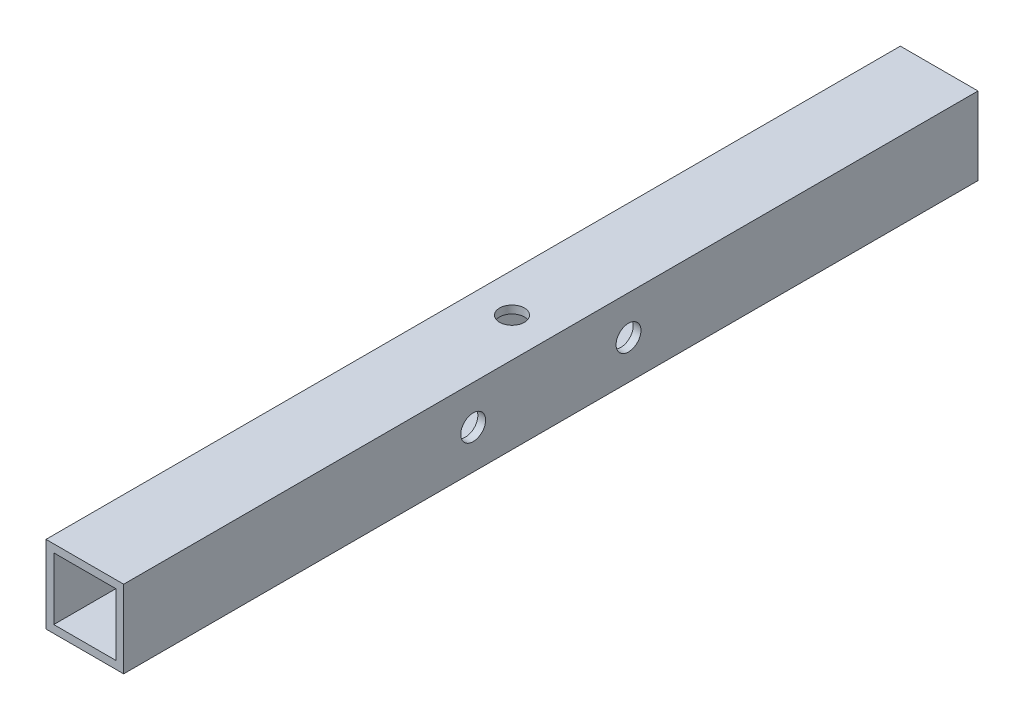
SolidWorks part; units mm, degrees
ref_plane "正面" through (0, 0, 0) normal (0, 0, 1) x (1, 0, 0)
ref_plane "平面" through (0, 0, 0) normal (0, 1, 0) x (1, 0, 0)
ref_plane "右側面" through (0, 0, 0) normal (1, 0, 0) x (0, 0, -1)
sketch "ｽｹｯﾁ1" plane through (0, 0, 0) normal (0, 0, 1) x (1, 0, 0)
  line L1 (-5, -5) -> (5, -5)
  line L2 (-5, -5) -> (-5, 5)
  line L3 (-5, 5) -> (5, 5)
  line L4 (5, -5) -> (5, 5)
  line L5 (-5, -5) -> (5, 5) construction
  line L6 (-5, 5) -> (5, -5) construction
  line L7 (-4, -4) -> (4, -4)
  line L8 (-4, -4) -> (-4, 4)
  line L9 (-4, 4) -> (4, 4)
  line L10 (4, -4) -> (4, 4)
  line L11 (-4, -4) -> (4, 4) construction
  line L12 (-4, 4) -> (4, -4) construction
  point P0 (0, 0)
  point P6 (0, 0)
  dimension "D1" = 10
  dimension "D2" = 10
  dimension "D3" = 1
extrude "ﾎﾞｽ - 押し出し1" add sketch "ｽｹｯﾁ1" along normal blind 110
sketch "ｽｹｯﾁ2" plane through (0, 5, 0) normal (0, 1, 0) x (1, 0, 0)
  line L0 (5, -110) -> (5, 0) construction
  circle A0 centre (0, -55) radius 1.6
  point P4 (5, -55)
  dimension "D1" = 3.2
  dimension "D2" = 0
  dimension "D3" = 5
extrude "ｶｯﾄ - 押し出し1" cut sketch "ｽｹｯﾁ2" against normal through all
sketch "ｽｹｯﾁ3" plane through (5, 0, 0) normal (1, 0, 0) x (0, 0, -1)
  line L0 (-45, 0) -> (-65, 0) construction
  line L1 (-110, -5) -> (0, -5) construction
  line L2 (-110, 5) -> (0, 5) construction
  circle A0 centre (-65, 0) radius 1.6
  circle A1 centre (-45, 0) radius 1.6
  point P4 (-55, 0)
  point P7 (-55, -5)
  dimension "D1" = 20
  dimension "D4" = 3.2
  dimension "D5" = 3.2
  dimension "D2" = 0
  dimension "D3" = 5
extrude "ｶｯﾄ - 押し出し2" cut sketch "ｽｹｯﾁ3" against normal through all
